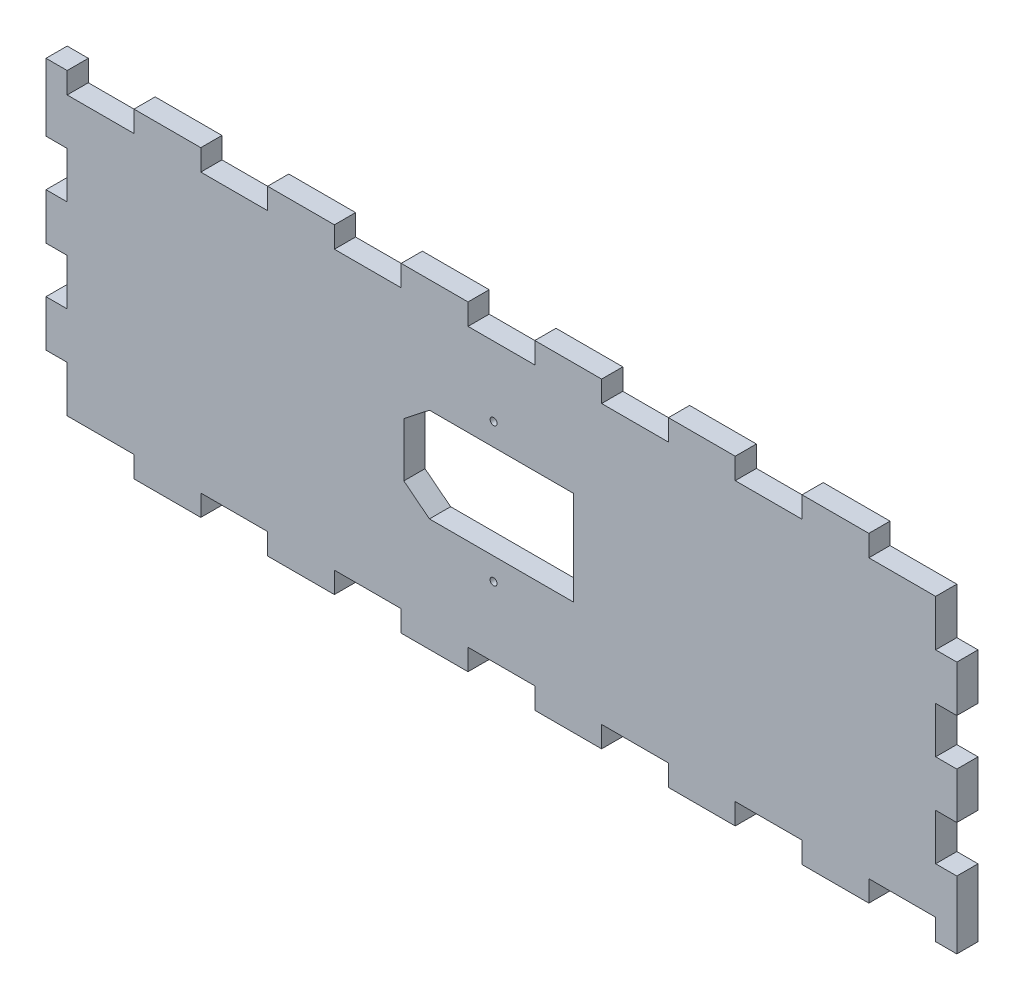
SolidWorks part; units mm, degrees
ref_plane "Front Plane" through (0, 0, 0) normal (0, 0, 1) x (1, 0, 0)
ref_plane "Top Plane" through (0, 0, 0) normal (0, 1, 0) x (1, 0, 0)
ref_plane "Right Plane" through (0, 0, 0) normal (1, 0, 0) x (0, 0, -1)
sketch "Sketch1" plane through (0, 0, 0) normal (0, 0, 1) x (1, 0, 0)
  line L0 (57.6923, 80) -> (76.9231, 80)
  line L1 (0, 0) -> (250, 0)
  line L2 (0, 0) -> (0, 80)
  line L3 (0, 80) -> (250, 80)
  line L4 (250, 0) -> (250, 80)
  line L5 (19.2308, 80) -> (38.4615, 80)
  line L6 (19.2308, 80) -> (19.2308, 86.096)
  line L7 (19.2308, 86.096) -> (38.4615, 86.096)
  line L8 (38.4615, 80) -> (38.4615, 86.096)
  line L9 (57.6923, 80) -> (57.6923, 86.096)
  line L10 (57.6923, 86.096) -> (76.9231, 86.096)
  line L11 (76.9231, 80) -> (76.9231, 86.096)
  line L12 (96.1538, 80) -> (115.3846, 80)
  line L13 (96.1538, 80) -> (96.1538, 86.096)
  line L14 (96.1538, 86.096) -> (115.3846, 86.096)
  line L15 (115.3846, 80) -> (115.3846, 86.096)
  line L16 (134.6154, 80) -> (153.8462, 80)
  line L17 (134.6154, 80) -> (134.6154, 86.096)
  line L18 (134.6154, 86.096) -> (153.8462, 86.096)
  line L19 (153.8462, 80) -> (153.8462, 86.096)
  line L20 (173.0769, 80) -> (192.3077, 80)
  line L21 (173.0769, 80) -> (173.0769, 86.096)
  line L22 (173.0769, 86.096) -> (192.3077, 86.096)
  line L23 (192.3077, 80) -> (192.3077, 86.096)
  line L24 (211.5385, 80) -> (230.7692, 80)
  line L25 (211.5385, 80) -> (211.5385, 86.096)
  line L26 (211.5385, 86.096) -> (230.7692, 86.096)
  line L27 (230.7692, 80) -> (230.7692, 86.096)
  line L28 (19.2308, 80) -> (0, 80) construction
  line L29 (230.7692, 80) -> (250, 80) construction
  line L30 (38.4615, 86.096) -> (57.6923, 86.096) construction
  line L31 (0, 40) -> (250, 40) construction
  line L32 (211.5385, 0) -> (211.5385, -6.096)
  line L33 (211.5385, -6.096) -> (230.7692, -6.096)
  line L34 (230.7692, 0) -> (230.7692, -6.096)
  line L35 (211.5385, 0) -> (230.7692, 0)
  line L36 (173.0769, 0) -> (173.0769, -6.096)
  line L37 (173.0769, -6.096) -> (192.3077, -6.096)
  line L38 (192.3077, 0) -> (192.3077, -6.096)
  line L39 (173.0769, 0) -> (192.3077, 0)
  line L40 (134.6154, 0) -> (134.6154, -6.096)
  line L41 (134.6154, -6.096) -> (153.8462, -6.096)
  line L42 (153.8462, 0) -> (153.8462, -6.096)
  line L43 (134.6154, 0) -> (153.8462, 0)
  line L44 (96.1538, 0) -> (96.1538, -6.096)
  line L45 (96.1538, -6.096) -> (115.3846, -6.096)
  line L46 (115.3846, 0) -> (115.3846, -6.096)
  line L47 (96.1538, 0) -> (115.3846, 0)
  line L48 (57.6923, 0) -> (57.6923, -6.096)
  line L49 (57.6923, -6.096) -> (76.9231, -6.096)
  line L50 (76.9231, 0) -> (76.9231, -6.096)
  line L51 (57.6923, 0) -> (76.9231, 0)
  line L52 (19.2308, -6.096) -> (38.4615, -6.096)
  line L53 (38.4615, 0) -> (38.4615, -6.096)
  line L54 (19.2308, 0) -> (38.4615, 0)
  line L55 (19.2308, 0) -> (19.2308, -6.096)
  line L56 (-6.096, 26.6667) -> (-6.096, 40) construction
  line L57 (0, 80) -> (-6.096, 80)
  line L58 (0, 80) -> (0, 66.6667)
  line L59 (0, 66.6667) -> (-6.096, 66.6667)
  line L60 (-6.096, 80) -> (-6.096, 66.6667)
  line L61 (0, 53.3333) -> (-6.096, 53.3333)
  line L62 (0, 53.3333) -> (0, 40)
  line L63 (0, 40) -> (-6.096, 40)
  line L64 (-6.096, 53.3333) -> (-6.096, 40)
  line L65 (0, 26.6667) -> (-6.096, 26.6667)
  line L66 (0, 26.6667) -> (0, 13.3333)
  line L67 (0, 13.3333) -> (-6.096, 13.3333)
  line L68 (-6.096, 26.6667) -> (-6.096, 13.3333)
  line L69 (-6.096, 53.3333) -> (-6.096, 66.6667) construction
  line L70 (-6.096, 13.3333) -> (-6.096, 0) construction
  line L71 (256.096, 13.3333) -> (256.096, 26.6667) construction
  line L72 (250, 0) -> (256.096, 0)
  line L73 (250, 0) -> (250, 13.3333)
  line L74 (250, 13.3333) -> (256.096, 13.3333)
  line L75 (256.096, 0) -> (256.096, 13.3333)
  line L76 (250, 26.6667) -> (256.096, 26.6667)
  line L77 (250, 26.6667) -> (250, 40)
  line L78 (250, 40) -> (256.096, 40)
  line L79 (256.096, 26.6667) -> (256.096, 40)
  line L80 (250, 53.3333) -> (256.096, 53.3333)
  line L81 (250, 53.3333) -> (250, 66.6667)
  line L82 (250, 66.6667) -> (256.096, 66.6667)
  line L83 (256.096, 53.3333) -> (256.096, 66.6667)
  line L84 (256.096, 40) -> (256.096, 53.3333) construction
  line L85 (256.096, 66.6667) -> (256.096, 80) construction
  line L87 (-6.096, 80) -> (0, 80)
  line L88 (-6.096, 80) -> (-6.096, 86.096)
  line L89 (-6.096, 86.096) -> (0, 86.096)
  line L90 (0, 80) -> (0, 86.096)
  line L91 (256.096, 0) -> (250, 0)
  line L92 (256.096, 0) -> (256.096, -6.096)
  line L93 (256.096, -6.096) -> (250, -6.096)
  line L94 (250, 0) -> (250, -6.096)
  dimension "D1" = 80
  dimension "D2" = 250
  dimension "D4" = 6.096
  dimension "D3" = 6
extrude "Boss-Extrude1" add sketch "Sketch1" along normal blind 6.096 contours L1 L4 L3 L0 L2 | L3 L8 L7 L6 | L57 L60 L59 L2 | L57 L90 L89 L88 | L61 L64 L63 L2 | L65 L68 L67 L2 | L1 L55 L52 L53 | L50 L1 L48 L49 | L46 L1 L44 L45 | L42 L1 L40 L41 | L38 L1 L36 L37 | L34 L1 L32 L33 | L72 L75 L74 L4 | L72 L94 L93 L92 | L76 L79 L78 L4 | L80 L83 L82 L4 | L3 L27 L26 L25 | L3 L23 L22 L21 | L3 L19 L18 L17 | L3 L15 L14 L13 | L0 L11 L10 L9
sketch "Sketch2" plane through (0, 0, 6.096) normal (0, 0, 1) x (1, 0, 0)
  line L0 (145.72, 53.5509) -> (104.28, 53.5509)
  line L1 (104.28, 53.5509) -> (96.9106, 47.7597)
  line L2 (96.9106, 47.7597) -> (96.9106, 32.2403)
  line L3 (96.9106, 32.2403) -> (104.28, 26.4491)
  line L4 (104.28, 26.4491) -> (145.72, 26.4491)
  line L5 (145.72, 26.4491) -> (145.72, 53.5509)
  line L6 (122.7504, 20.0394) -> (122.7504, 59.9606) construction
  line L7 (250, 80) -> (250, 0) construction
  line L8 (0, 80) -> (250, 80) construction
  circle A0 centre (122.7504, 59.9606) radius 1
  circle A1 centre (122.7504, 20.0394) radius 1
  point P7 (96.9106, 40)
  point P8 (145.72, 40)
  point P10 (250, 40)
  point P12 (122.7504, 40)
  point P14 (125, 80)
  point P15 (125, 53.5509)
  point P20 (124.9617, 64.6473)
  dimension "D7" = 2
  dimension "D1" = 27.1018
  dimension "D2" = 48.8095
  dimension "D3" = 9.3726
  dimension "D4" = 15.5194
  dimension "D5" = 25.8398
  dimension "D6" = 6.4097
extrude "Cut-Extrude1" cut sketch "Sketch2" against normal through all
